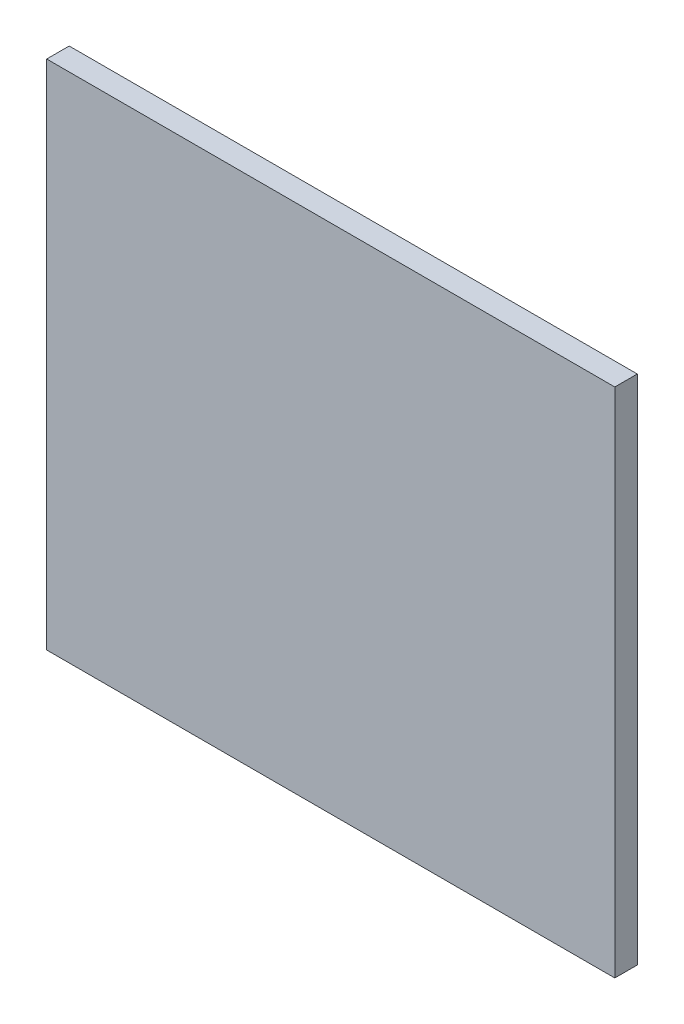
SolidWorks part; units mm, degrees
ref_plane "Piano frontale" through (0, 0, 0) normal (0, 0, 1) x (1, 0, 0)
ref_plane "Piano superiore" through (0, 0, 0) normal (0, 1, 0) x (1, 0, 0)
ref_plane "Piano destro" through (0, 0, 0) normal (1, 0, 0) x (0, 0, -1)
sketch "Schizzo1" plane through (0, 0, 0) normal (0, 0, 1) x (1, 0, 0)
  line L1 (0, 0) -> (50.5, 0)
  line L2 (0, 0) -> (0, 45.5)
  line L3 (0, 45.5) -> (50.5, 45.5)
  line L4 (50.5, 0) -> (50.5, 45.5)
  dimension "D1" = 50.5
  dimension "D2" = 45.5
extrude "Estrusione-Estrusione1" add sketch "Schizzo1" along normal blind 2
